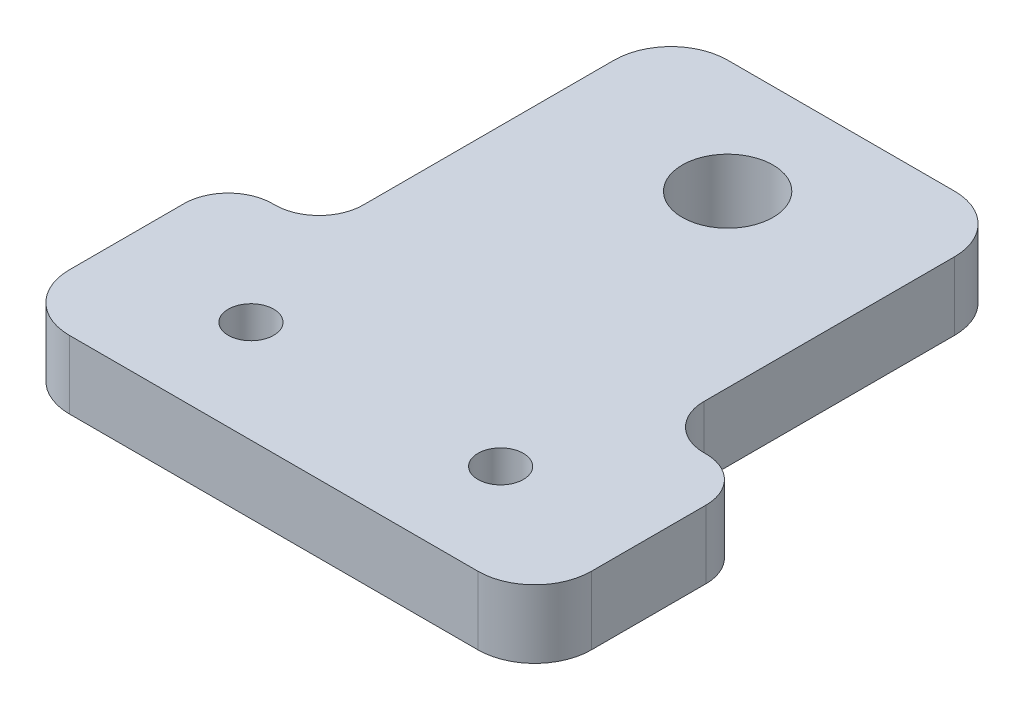
SolidWorks part; units mm, degrees
ref_plane "Front Plane" through (0, 0, 0) normal (0, 0, 1) x (1, 0, 0)
ref_plane "Top Plane" through (0, 0, 0) normal (0, 1, 0) x (1, 0, 0)
ref_plane "Right Plane" through (0, 0, 0) normal (1, 0, 0) x (0, 0, -1)
sketch "Sketch1" plane through (0, 0, 0) normal (0, 1, 0) x (1, 0, 0)
  line L0 (0, 0) -> (0, 46.5158) construction
  line L1 (-23, 0) -> (23, 0)
  line L2 (23, 0) -> (23, 19)
  line L3 (23, 19) -> (15, 19)
  line L4 (15, 19) -> (15, 50)
  line L5 (15, 50) -> (-15, 50)
  line L6 (-23, 0) -> (-23, 19)
  line L7 (-23, 19) -> (-15, 19)
  line L8 (-15, 19) -> (-15, 50)
  circle A0 centre (0, 40) radius 4
  circle A1 centre (11, 9) radius 2
  circle A2 centre (-11, 9) radius 2
  point P13 (0, 23.2579)
  point P20 (0, 50)
  dimension "D1" = 8
  dimension "D9" = 4
  dimension "D2" = 22
  dimension "D3" = 9
  dimension "D4" = 19
  dimension "D5" = 31
  dimension "D6" = 50
  dimension "D7" = 15
  dimension "D8" = 8
extrude "Boss-Extrude1" add sketch "Sketch1" along normal blind 6
fillet "Fillet2" radius 5 4 edges at (-15, 3, -50) (15, 3, -50) (-23, 3, 0) (23, 3, 0)
fillet "Fillet3" radius 3.9 4 edges at (-23, 3, -19) (-15, 3, -19) (23, 3, -19) (15, 3, -19)
